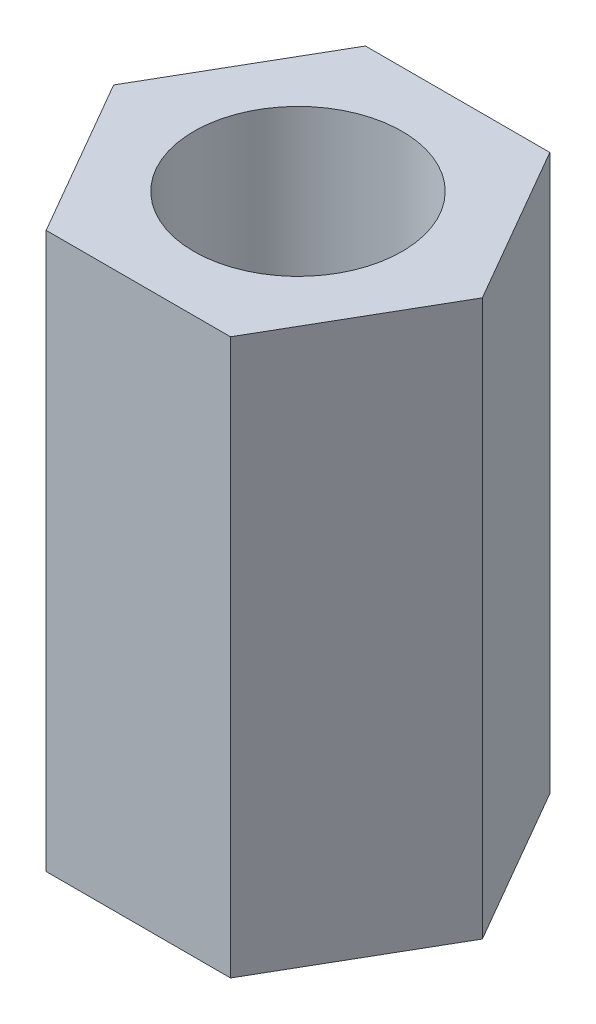
SolidWorks part; units mm, degrees
material "黄铜"
ref_plane "前视基准面" through (0, 0, 0) normal (0, 0, 1) x (1, 0, 0)
ref_plane "上视基准面" through (0, 0, 0) normal (0, 1, 0) x (1, 0, 0)
ref_plane "右视基准面" through (0, 0, 0) normal (1, 0, 0) x (0, 0, -1)
sketch "草图1" plane through (0, 0, 0) normal (0, 1, 0) x (1, 0, 0)
  line L1 (2.6558, 0) -> (1.3279, 2.3)
  line L2 (1.3279, 2.3) -> (-1.3279, 2.3)
  line L3 (-1.3279, 2.3) -> (-2.6558, 0)
  line L4 (-2.6558, 0) -> (-1.3279, -2.3)
  line L5 (-1.3279, -2.3) -> (1.3279, -2.3)
  line L6 (1.3279, -2.3) -> (2.6558, 0)
  circle A0 centre (0, 0) radius 2.3 construction
  dimension "D1" = 4.6
extrude "凸台-拉伸1" add sketch "草图1" along normal blind 8
sketch "草图2" plane through (0, 8, 0) normal (0, 1, 0) x (1, 0, 0)
  point P0 (0, 0)
hole_wizard "孔1" positions "草图2" profile "草图3" legacy end condition through all
sketch "草图3" plane through (0, 8, 0) normal (1, 0, 0) x (0, 0, 1)
  line L0 (0, 0) -> (0, 8)
  line L1 (0, 8) -> (1.5, 8)
  line L2 (1.5, 8) -> (1.5, 0)
  line L3 (1.5, 0) -> (0, 0)
  line L4 (0, 110) -> (0, -10) construction
  dimension "直径" = 3
  dimension "深度" = 8
